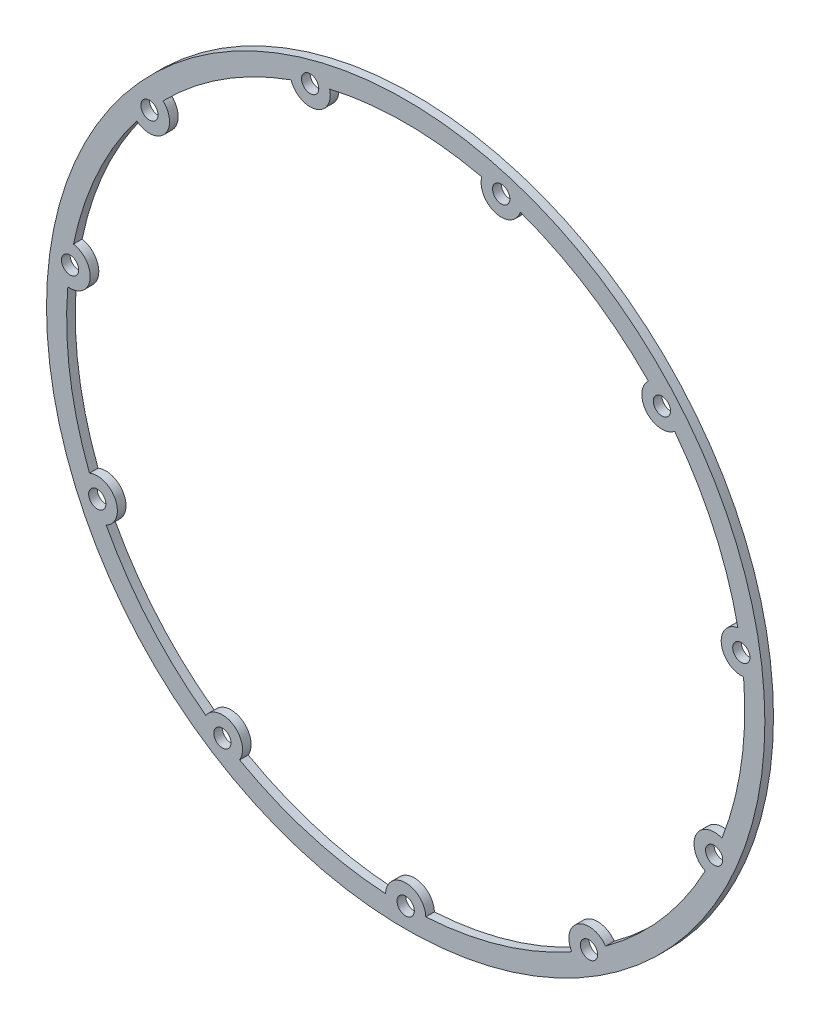
SolidWorks part; units mm, degrees
ref_plane "前视基准面" through (0, 0, 0) normal (0, 0, 1) x (1, 0, 0)
ref_plane "上视基准面" through (0, 0, 0) normal (0, 1, 0) x (1, 0, 0)
ref_plane "右视基准面" through (0, 0, 0) normal (1, 0, 0) x (0, 0, -1)
sketch "草图1" plane through (0, 0, 0) normal (0, 0, 1) x (1, 0, 0)
  line L0 (0, -59) -> (0, 0) construction
  line L1 (0, 0) -> (21.3581, 0) construction
  circle A1 centre (0, 0) radius 62.5
  circle A2 centre (0, 0) radius 59 construction
  circle A3 centre (0, -59) radius 1.5
  circle A4 centre (0, -59) radius 3.5 construction
  arc A5 (3.4985, -58.8962) -> (-3.4985, -58.8962) centre (0, -59) ccw
  circle A6 centre (-31.8978, -49.634) radius 1.5
  circle A7 centre (-53.6683, -24.5095) radius 1.5
  circle A8 centre (-58.3995, 8.3966) radius 1.5
  circle A9 centre (-44.5892, 38.6368) radius 1.5
  circle A10 centre (-16.6222, 56.6101) radius 1.5
  circle A11 centre (16.6222, 56.6101) radius 1.5
  circle A12 centre (44.5892, 38.6368) radius 1.5
  circle A13 centre (58.3995, 8.3966) radius 1.5
  circle A14 centre (53.6683, -24.5095) radius 1.5
  circle A15 centre (31.8978, -49.634) radius 1.5
  circle A16 centre (31.8978, -49.634) radius 3.5 construction
  arc A17 (28.8986, -51.438) -> (3.4985, -58.8962) centre (0, 0) cw
  arc A18 (-3.4985, -58.8962) -> (-28.8986, -51.438) centre (0, 0) cw
  arc A19 (-28.8986, -51.438) -> (-34.7848, -47.6552) centre (-31.8978, -49.634) ccw
  arc A20 (-34.7848, -47.6552) -> (-52.1205, -27.6487) centre (0, 0) cw
  arc A21 (-52.1205, -27.6487) -> (-55.0272, -21.284) centre (-53.6683, -24.5095) ccw
  arc A22 (-55.0272, -21.284) -> (-58.7946, 4.919) centre (0, 0) cw
  arc A23 (-58.7946, 4.919) -> (-57.7988, 11.8447) centre (-58.3995, 8.3966) ccw
  arc A24 (-57.7988, 11.8447) -> (-46.8018, 35.9248) centre (0, 0) cw
  arc A25 (-46.8018, 35.9248) -> (-42.2198, 41.2128) centre (-44.5892, 38.6368) ccw
  arc A26 (-42.2198, 41.2128) -> (-19.9497, 55.5248) centre (0, 0) cw
  arc A27 (-19.9497, 55.5248) -> (-13.2362, 57.4961) centre (-16.6222, 56.6101) ccw
  arc A28 (-13.2362, 57.4961) -> (13.2362, 57.4961) centre (0, 0) cw
  arc A29 (13.2362, 57.4961) -> (19.9497, 55.5248) centre (16.6222, 56.6101) ccw
  arc A30 (19.9497, 55.5248) -> (42.2198, 41.2128) centre (0, 0) cw
  arc A31 (42.2198, 41.2128) -> (46.8018, 35.9248) centre (44.5892, 38.6368) ccw
  arc A32 (46.8018, 35.9248) -> (57.7988, 11.8447) centre (0, 0) cw
  arc A33 (57.7988, 11.8447) -> (58.7946, 4.919) centre (58.3995, 8.3966) ccw
  arc A34 (58.7946, 4.919) -> (55.0272, -21.284) centre (0, 0) cw
  arc A35 (55.0272, -21.284) -> (52.1205, -27.6487) centre (53.6683, -24.5095) ccw
  arc A36 (52.1205, -27.6487) -> (34.7848, -47.6552) centre (0, 0) cw
  arc A37 (34.7848, -47.6552) -> (28.8986, -51.438) centre (31.8978, -49.634) ccw
  point P7 (0, 0)
  dimension "D1" = 11
  dimension "D2" = 125
  dimension "D3" = 118
  dimension "D4" = 3
  dimension "D5" = 11
extrude "凸台-拉伸1" add sketch "草图1" along normal blind 1.5 contours A4
